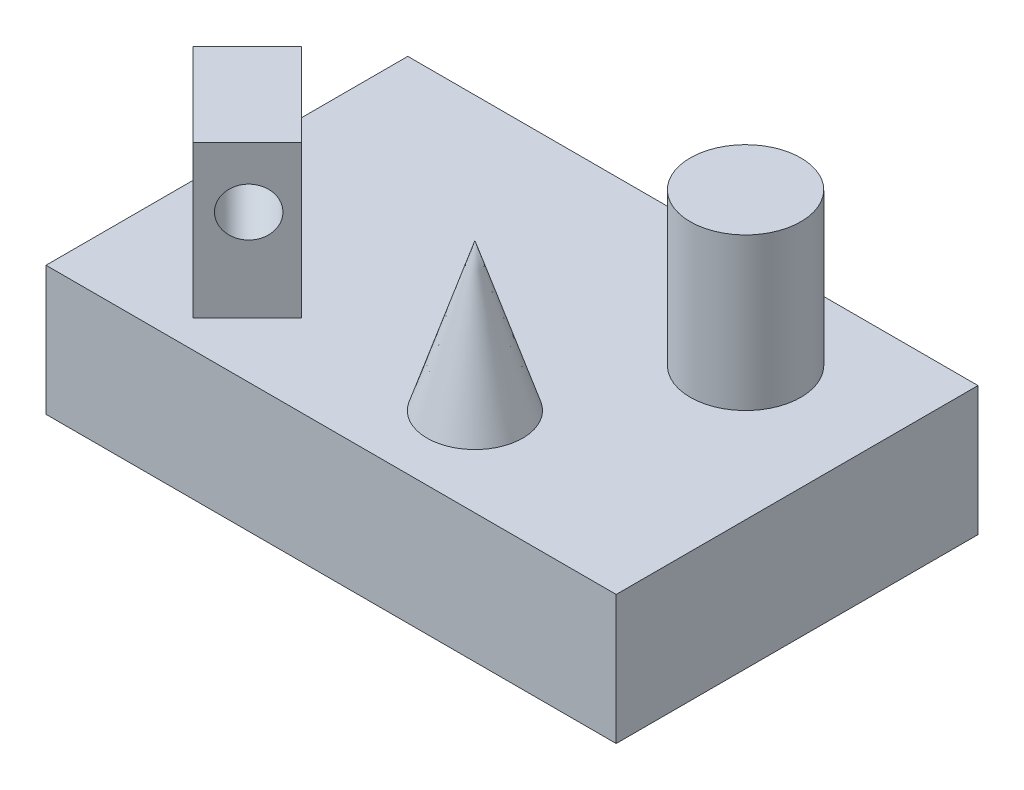
SolidWorks part; units mm, degrees
other "Videocamera1"
ref_plane "Piano frontale" through (0, 0, 0) normal (0, 0, 1) x (1, 0, 0)
ref_plane "Piano superiore" through (0, 0, 0) normal (0, 1, 0) x (1, 0, 0)
ref_plane "Piano destro" through (0, 0, 0) normal (1, 0, 0) x (0, 0, -1)
sketch "Schizzo1" plane through (0, 0, 0) normal (0, 1, 0) x (1, 0, 0)
  line L1 (0, 0) -> (56.2305, 0)
  line L2 (0, 0) -> (0, 35.6809)
  line L3 (0, 35.6809) -> (56.2305, 35.6809)
  line L4 (56.2305, 0) -> (56.2305, 35.6809)
extrude "Estrusione-Estrusione1" add sketch "Schizzo1" along normal blind 12.7353
sketch "Schizzo2" plane through (0, 12.7353, 0) normal (0, 1, 0) x (1, 0, 0)
  line L0 (3.5726, 10.9421) -> (8.9224, 16.2919)
  line L5 (8.9224, 16.2919) -> (17.1092, 8.1051)
  line L6 (17.1092, 8.1051) -> (11.7594, 2.7553)
  line L7 (11.7594, 2.7553) -> (3.5726, 10.9421)
extrude "Estrusione-Estrusione2" add sketch "Schizzo2" along normal blind 15 separate body
sketch "Schizzo3" plane through (0, 12.7353, 0) normal (0, 1, 0) x (1, 0, 0)
  circle A0 centre (43.0516, 25.9368) radius 5.4538
extrude "Estrusione-Estrusione3" add sketch "Schizzo3" along normal blind 15 separate body
sketch "Schizzo5" plane through (4.502, 0, 4.502) normal (0.7071, 0, 0.7071) x (0.7071, 0, -0.7071)
  circle A0 centre (14.135, 21.7763) radius 2.3887
extrude "Taglio-Estrusione1" cut sketch "Schizzo5" against normal through all both and the other way through all
sketch "Schizzo6" plane through (0, 12.7353, 0) normal (0, 1, 0) x (1, 0, 0)
  circle A0 centre (33.5593, 8.739) radius 4.7171
extrude "Estrusione-Estrusione4" add sketch "Schizzo6" along normal blind 15 draft 18 separate body
